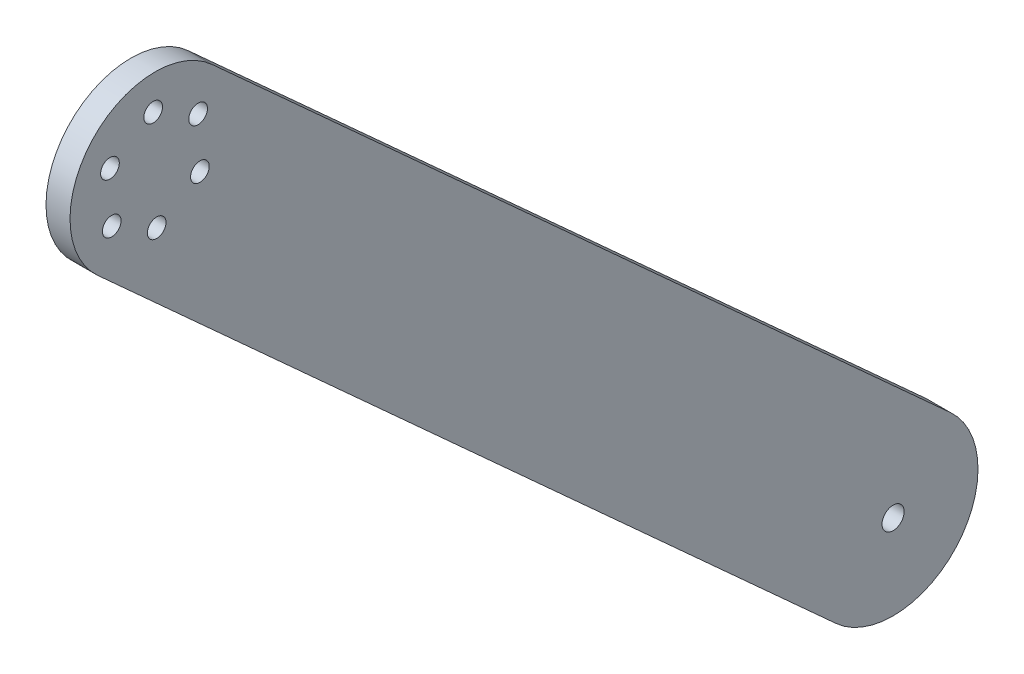
SolidWorks part; units mm, degrees
ref_plane "Front Plane" through (0, 0, 0) normal (0, 0, 1) x (1, 0, 0)
ref_plane "Top Plane" through (0, 0, 0) normal (0, 1, 0) x (1, 0, 0)
ref_plane "Right Plane" through (0, 0, 0) normal (1, 0, 0) x (0, 0, -1)
sketch "Sketch1" plane through (0, 0, 0) normal (1, 0, 0) x (0, 0, -1)
  line L0 (-231.1464, 0) -> (231.1464, 0) construction
  line L1 (0, -245.8185) -> (0, 245.8185) construction
  line L2 (-86.9435, 78.9642) -> (86.9435, -78.9642) construction
  line L3 (-73.497, 93.7693) -> (100.3899, -64.159)
  line L4 (-100.3899, 64.159) -> (73.497, -93.7693)
  arc A0 (-73.497, 93.7693) -> (-100.3899, 64.159) centre (-86.9435, 78.9642) ccw
  arc A1 (73.497, -93.7693) -> (100.3899, -64.159) centre (86.9435, -78.9642) ccw
  circle A2 centre (-86.9435, 78.9642) radius 12 construction
  circle A3 centre (86.9435, -78.9642) radius 2.6067
  circle A4 centre (-97.1226, 72.6092) radius 2.2
  circle A5 centre (-97.5366, 84.602) radius 2.2
  circle A6 centre (-87.3575, 90.957) radius 2.2
  circle A7 centre (-76.7644, 85.3191) radius 2.2
  circle A8 centre (-76.3503, 73.3263) radius 2.2
  circle A9 centre (-86.5294, 66.9713) radius 2.2
  point P7 (0, 0)
  point P16 (0, 0)
  point P17 (0, 0)
  dimension "D2" = 24
  dimension "D3" = 5.2134
  dimension "D7" = 4.4
  dimension "D1" = 40
  dimension "D4" = 234.9
  dimension "D5" = 491.637
  dimension "D6" = 462.2927
  dimension "D8" = 6
extrude "Boss-Extrude1" add sketch "Sketch1" along normal blind 5.661
